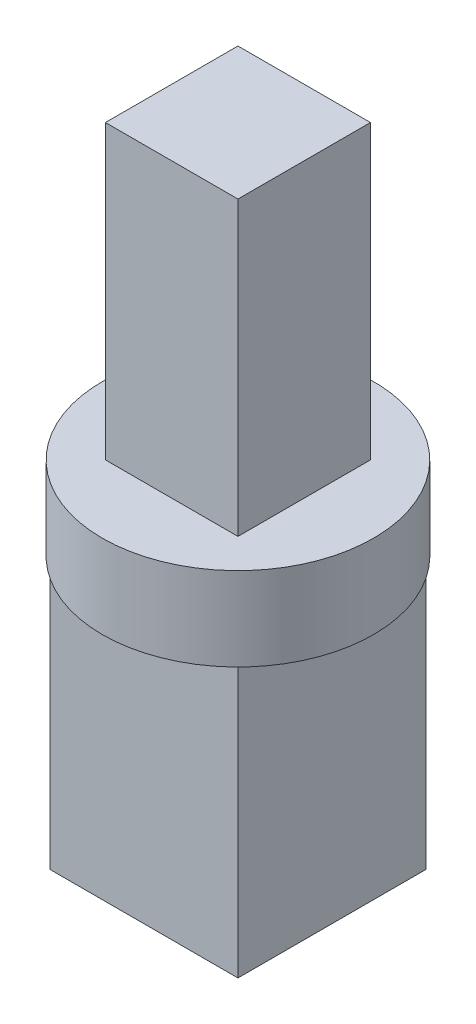
SolidWorks part; units mm, degrees
ref_plane "Front Plane" through (0, 0, 0) normal (0, 0, 1) x (1, 0, 0)
ref_plane "Top Plane" through (0, 0, 0) normal (0, 1, 0) x (1, 0, 0)
ref_plane "Right Plane" through (0, 0, 0) normal (1, 0, 0) x (0, 0, -1)
sketch "Sketch1" plane through (0, 0, 0) normal (0, 1, 0) x (1, 0, 0)
  circle A0 centre (0, 0) radius 6.5
  dimension "D1" = 13
extrude "Boss-Extrude1" add sketch "Sketch1" along normal blind 4
sketch "Sketch2" plane through (0, 4, 0) normal (0, 1, 0) x (1, 0, 0)
  line L1 (-3.175, -3.175) -> (3.175, -3.175)
  line L2 (-3.175, -3.175) -> (-3.175, 3.175)
  line L3 (-3.175, 3.175) -> (3.175, 3.175)
  line L4 (3.175, -3.175) -> (3.175, 3.175)
  line L5 (-3.175, -3.175) -> (3.175, 3.175) construction
  line L6 (-3.175, 3.175) -> (3.175, -3.175) construction
  point P0 (0, 0)
  dimension "D1" = 6.35
  dimension "D2" = 6.35
extrude "Boss-Extrude2" add sketch "Sketch2" along normal blind 14
sketch "Sketch3" plane through (0, 0, 0) normal (0, -1, 0) x (1, 0, 0)
  line L1 (-4.5, -4.5) -> (4.5, -4.5)
  line L2 (-4.5, -4.5) -> (-4.5, 4.5)
  line L3 (-4.5, 4.5) -> (4.5, 4.5)
  line L4 (4.5, -4.5) -> (4.5, 4.5)
  line L5 (-4.5, -4.5) -> (4.5, 4.5) construction
  line L6 (-4.5, 4.5) -> (4.5, -4.5) construction
  point P0 (0, 0)
  dimension "D1" = 9
  dimension "D2" = 9
extrude "Boss-Extrude3" add sketch "Sketch3" along normal blind 13
